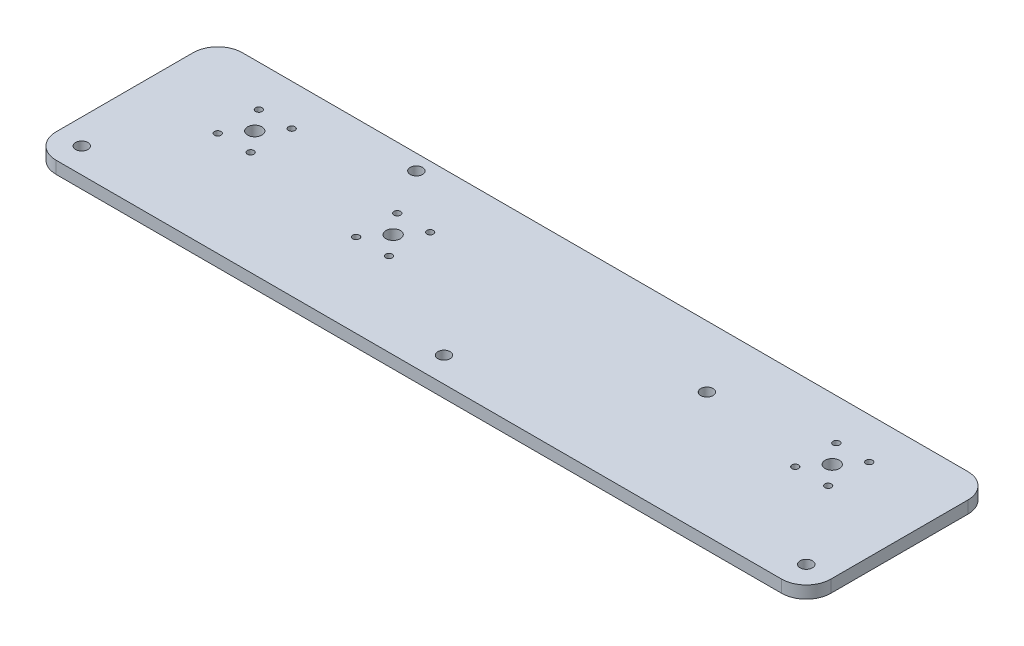
SolidWorks part; units mm, degrees
material "Policarbonato"
ref_plane "Plano frontal" through (0, 0, 0) normal (0, 0, 1) x (1, 0, 0)
ref_plane "Plano superior" through (0, 0, 0) normal (0, 1, 0) x (1, 0, 0)
ref_plane "Plano direito" through (0, 0, 0) normal (1, 0, 0) x (0, 0, -1)
sketch "Esboço1" plane through (0, 0, 0) normal (0, 1, 0) x (1, 0, 0)
  line L4 (132.965, 0) -> (148.965, 0) construction
  line L6 (188.965, -38.6487) -> (188.965, 28)
  line L7 (176.965, 40) -> (-176.0908, 40)
  line L8 (-188.0908, 28) -> (-188.0908, -38.6487)
  line L9 (132.965, 0) -> (132.965, 20) construction
  line L11 (132.965, 20) -> (148.965, 20) construction
  line L12 (148.965, 0) -> (148.965, 20) construction
  line L13 (132.965, 0) -> (148.965, 20) construction
  line L14 (132.965, 20) -> (148.965, 0) construction
  line L15 (-148.0908, 0) -> (-132.0908, 0) construction
  line L16 (-148.0908, 0) -> (-148.0908, 20) construction
  line L17 (-148.0908, 20) -> (-132.0908, 20) construction
  line L18 (-132.0908, 0) -> (-132.0908, 20) construction
  line L19 (-176.0908, -50.6487) -> (176.965, -50.6487)
  line L20 (-148.0908, 0) -> (-132.0908, 20) construction
  line L21 (-148.0908, 20) -> (-132.0908, 0) construction
  line L22 (-70.7345, -10) -> (-54.7345, -10) construction
  line L23 (-70.7345, -10) -> (-70.7345, 10) construction
  line L24 (-70.7345, 10) -> (-54.7345, 10) construction
  line L25 (-54.7345, -10) -> (-54.7345, 10) construction
  line L26 (-70.7345, -10) -> (-54.7345, 10) construction
  line L27 (-70.7345, 10) -> (-54.7345, -10) construction
  arc A0 (176.965, -50.6487) -> (188.965, -38.6487) centre (176.965, -38.6487) ccw
  arc A1 (188.965, 28) -> (176.965, 40) centre (176.965, 28) ccw
  arc A2 (-188.0908, 28) -> (-176.0908, 40) centre (-176.0908, 28) cw
  arc A3 (-188.0908, -38.6487) -> (-176.0908, -50.6487) centre (-176.0908, -38.6487) ccw
  circle A7 centre (-62.7345, 0) radius 3.5
  circle A8 centre (176.7481, -38.4318) radius 3
  circle A9 centre (0.4371, -38.4318) radius 3
  circle A10 centre (79.965, 10) radius 3
  circle A11 centre (-140.0908, 10) radius 3.5
  circle A13 centre (-148.0908, 0) radius 1.6
  circle A14 centre (-132.0908, 0) radius 1.6
  circle A15 centre (-132.0908, 20) radius 1.6
  circle A16 centre (-148.0908, 20) radius 1.6
  circle A17 centre (-70.7345, -10) radius 1.6
  circle A18 centre (-70.7345, 10) radius 1.6
  circle A19 centre (-54.7345, 10) radius 1.6
  circle A20 centre (-54.7345, -10) radius 1.6
  circle A21 centre (-62.7345, 0) radius 25 construction
  circle A22 centre (-83.9303, 32.5) radius 7.5 construction
  circle A23 centre (-140.0908, 10) radius 48 construction
  circle A24 centre (-83.9303, 32.5) radius 3
  circle A25 centre (-175.8739, -38.4318) radius 3
  circle A26 centre (140.965, 10) radius 3.5
  circle A27 centre (148.965, 0) radius 1.6
  circle A28 centre (148.965, 20) radius 1.6
  circle A29 centre (132.965, 0) radius 1.6
  circle A30 centre (132.965, 20) radius 1.6
  point P33 (0.4371, 40)
  dimension "D2" = 377.0558
  dimension "D4" = 7
  dimension "D6" = 12.2169
  dimension "D8" = 203.9448
  dimension "D10" = 48
  dimension "D12" = 16
  dimension "D15" = 20
  dimension "D17" = 6
  dimension "D1" = 12
  dimension "D7" = 40
  dimension "D9" = 30
  dimension "D11" = 7
  dimension "D16" = 3.2
  dimension "D20" = 3.2
  dimension "D25" = 56.1605
  dimension "D26" = 61
  dimension "D27" = 50
  dimension "D28" = 15
  dimension "D29" = 96
  dimension "D3" = 90.6487
  dimension "D5" = 12.2169
  dimension "D13" = 16
  dimension "D14" = 20
  dimension "D18" = 12.2169
  dimension "D19" = 30
  dimension "D21" = 16
  dimension "D22" = 20
  dimension "D23" = 48
  dimension "D24" = 7.5
extrude "Ressalto-extrusão1" add sketch "Esboço1" against normal blind 6
